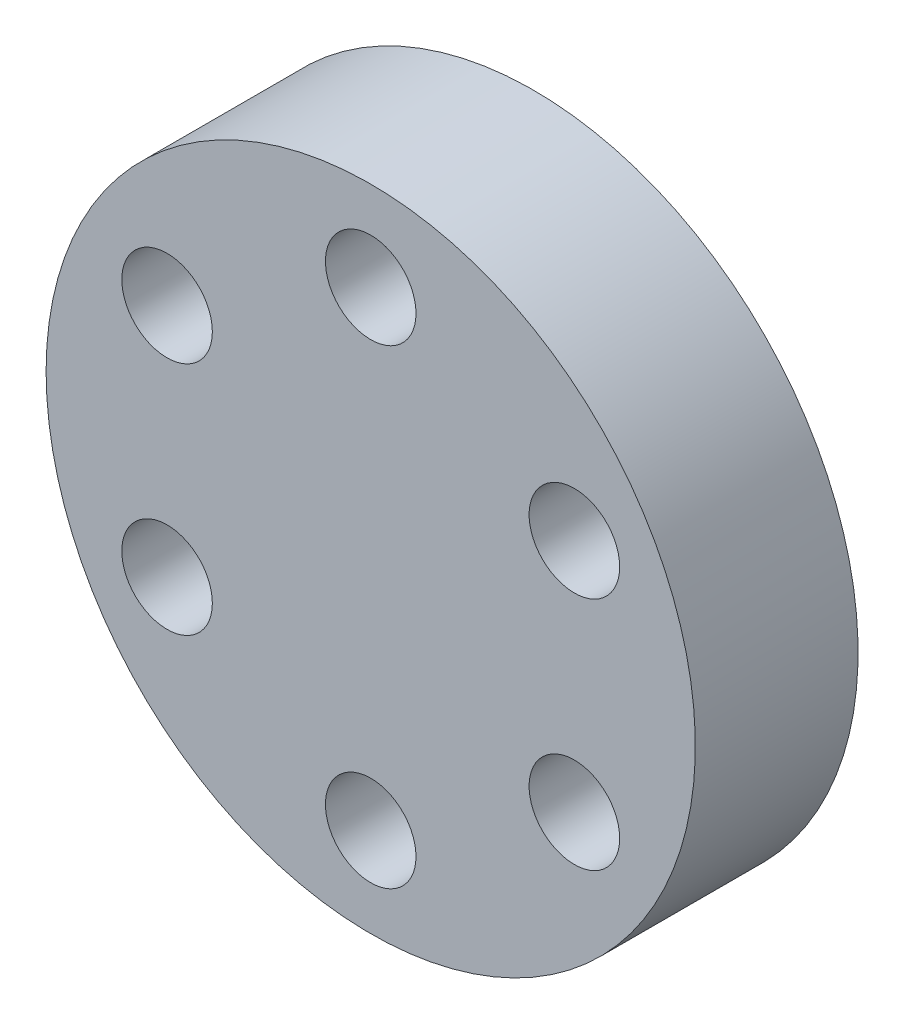
SolidWorks part; units mm, degrees
ref_plane "Front Plane" through (0, 0, 0) normal (0, 0, 1) x (1, 0, 0)
ref_plane "Top Plane" through (0, 0, 0) normal (0, 1, 0) x (1, 0, 0)
ref_plane "Right Plane" through (0, 0, 0) normal (1, 0, 0) x (0, 0, -1)
sketch "Sketch1" plane through (0, 0, 0) normal (0, 0, 1) x (1, 0, 0)
  circle A0 centre (0, 0) radius 19
  dimension "D1" = 38
extrude "Boss-Extrude1" add sketch "Sketch1" along normal blind 9.525
sketch "Sketch2" plane through (0, 0, 9.525) normal (0, 0, 1) x (1, 0, 0)
  circle A0 centre (0, 0) radius 13.7638 construction
  point P3 (0, 13.7638)
  point P4 (11.9198, 6.8819)
  point P7 (11.9198, -6.8819)
  point P8 (0, -13.7638)
  point P9 (-11.9198, -6.8819)
  point P10 (-11.9198, 6.8819)
  point P11 (0, 0)
  dimension "D1" = 6
hole_wizard "M5 Clearance Hole1" positions "Sketch2" profile "Sketch3" hole size "M5" standard "ANSI Metric"
sketch "Sketch3" plane through (-11.9198, 6.8819, 9.525) normal (1, 0, 0) x (0, -1, 0)
  line L0 (0, 0) -> (0, 9.525)
  line L1 (0, 9.525) -> (2.65, 9.525)
  line L2 (2.65, 9.525) -> (2.65, 0)
  line L5 (2.65, 0) -> (0, 0)
  line L11 (0, -6.35) -> (0, 107.95) construction
  dimension "Thru Hole Dia." = 5.3
  dimension "Thru Hole Depth" = 9.525
